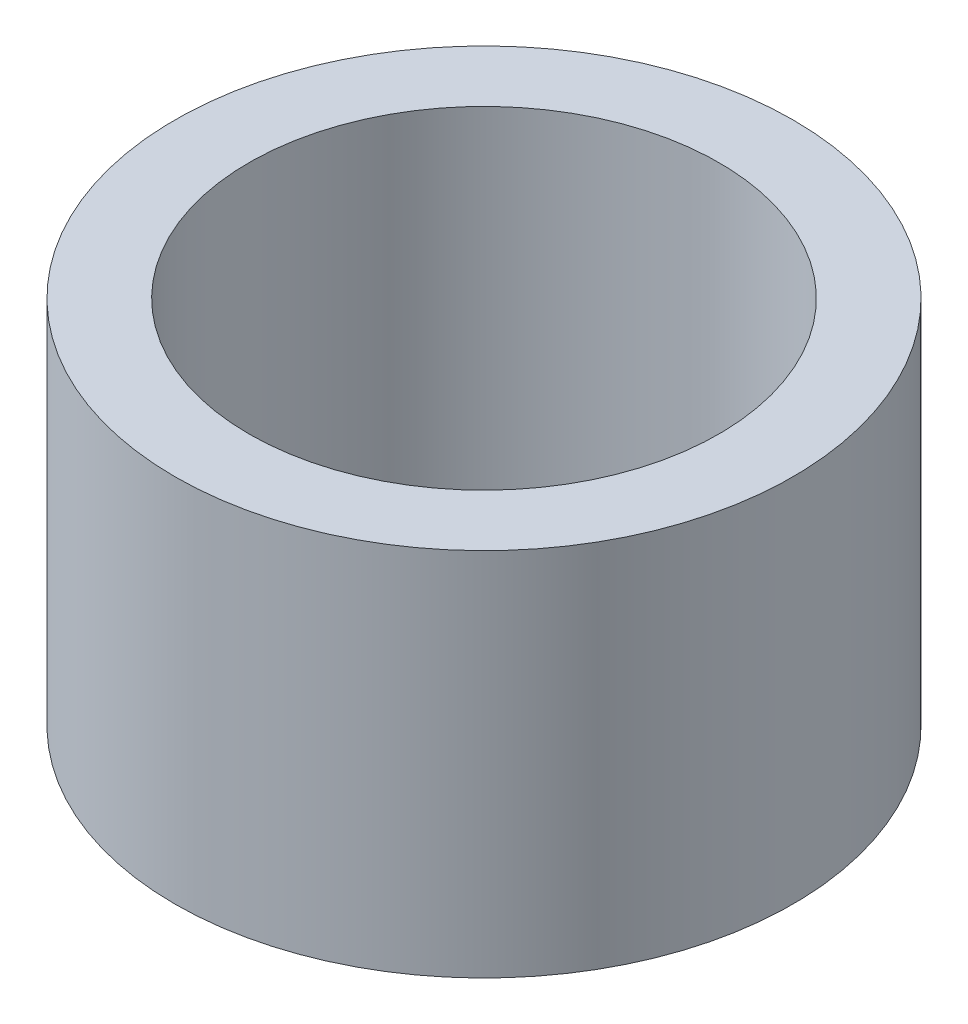
SolidWorks part; units mm, degrees
material "ABS"
ref_plane "Front Plane" through (0, 0, 0) normal (0, 0, 1) x (1, 0, 0)
ref_plane "Top Plane" through (0, 0, 0) normal (0, 1, 0) x (1, 0, 0)
ref_plane "Right Plane" through (0, 0, 0) normal (1, 0, 0) x (0, 0, -1)
sketch "Sketch1" plane through (0, 0, 0) normal (0, 1, 0) x (1, 0, 0)
  circle A0 centre (0, 0) radius 1.6129
  circle A1 centre (0, 0) radius 2.1209
  dimension "D1" = 3.2258
  dimension "D2" = 0.508
extrude "Boss-Extrude1" add sketch "Sketch1" along normal blind 2.54
